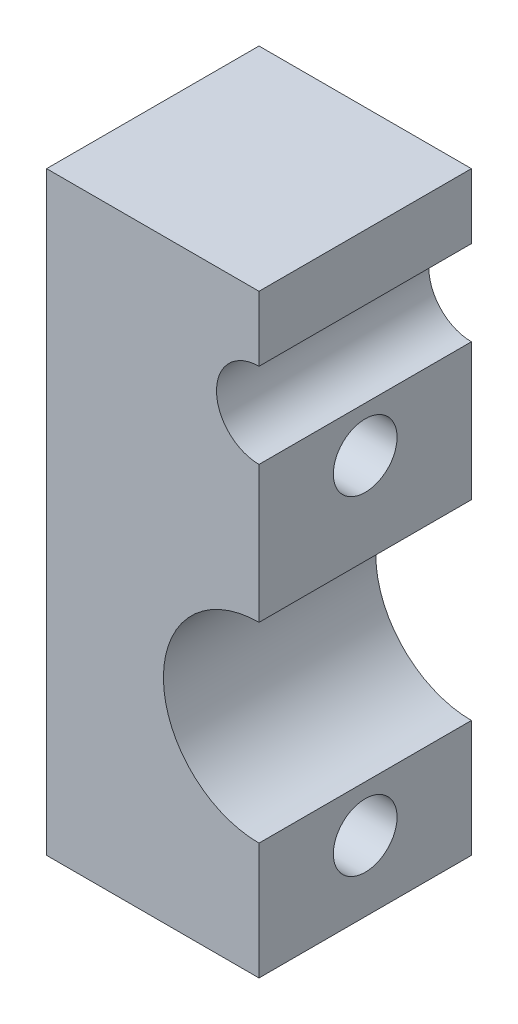
SolidWorks part; units mm, degrees
ref_plane "Спереди" through (0, 0, 0) normal (0, 0, 1) x (1, 0, 0)
ref_plane "Сверху" through (0, 0, 0) normal (0, 1, 0) x (1, 0, 0)
ref_plane "Справа" through (0, 0, 0) normal (1, 0, 0) x (0, 0, -1)
sketch "Эскиз1" plane through (0, 0, 0) normal (0, 1, 0) x (1, 0, 0)
  line L1 (-5, 5) -> (5, 5)
  line L2 (-5, 5) -> (-5, -5)
  line L3 (-5, -5) -> (5, -5)
  line L4 (5, 5) -> (5, -5)
  line L5 (-5, 5) -> (5, -5) construction
  line L6 (-5, -5) -> (5, 5) construction
  point P0 (0, 0)
extrude "Вытянуть1" add sketch "Эскиз1" along normal blind 28
sketch "Эскиз2" plane through (0, 0, 5) normal (0, 0, 1) x (1, 0, 0)
  line L0 (5, 28) -> (5, 0) construction
  circle A0 centre (5, 10) radius 4.5
extrude "Вытянуть2" cut sketch "Эскиз2" against normal through all
sketch "Эскиз3" plane through (5, 0, 0) normal (1, 0, 0) x (0, 0, -1)
  circle A0 centre (0, 3.3097) radius 1.5
  circle A1 centre (0, 18.7989) radius 1.5
extrude "Вырез-Вытянуть1" cut sketch "Эскиз3" against normal through all
sketch "Эскиз4" plane through (0, 0, 5) normal (0, 0, 1) x (1, 0, 0)
  line L0 (5, 28) -> (5, 14.5) construction
  line L1 (5, 28) -> (5, 14.5) construction
  circle A0 centre (5, 22.9407) radius 2
extrude "Вырез-Вытянуть2" cut sketch "Эскиз4" against normal through all
